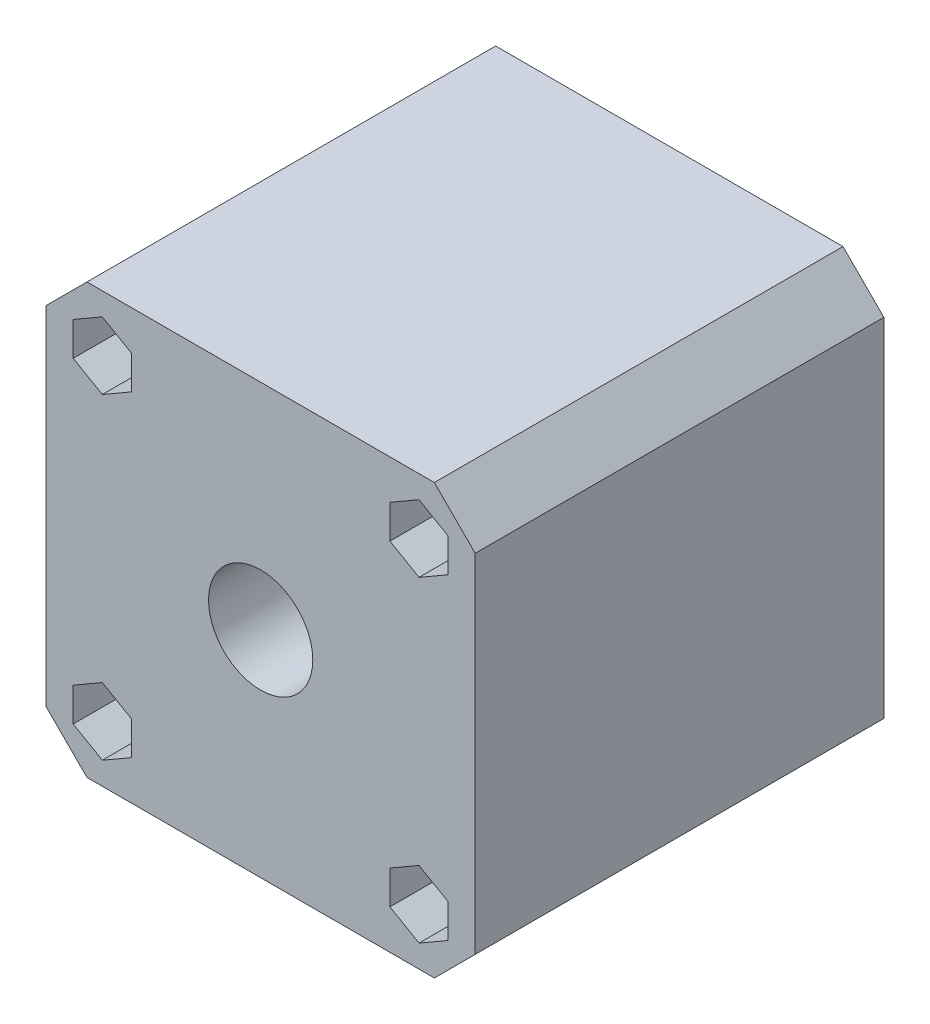
SolidWorks part; units mm, degrees
ref_plane "前基準面" through (0, 0, 0) normal (0, 0, 1) x (1, 0, 0)
ref_plane "上基準面" through (0, 0, 0) normal (0, 1, 0) x (1, 0, 0)
ref_plane "右基準面" through (0, 0, 0) normal (1, 0, 0) x (0, 0, -1)
sketch "草圖1" plane through (0, 0, 0) normal (0, 0, 1) x (1, 0, 0)
  line L0 (0, 21) -> (0, -21) construction
  line L1 (-21, 21) -> (21, 21)
  line L2 (-21, 21) -> (-21, -21)
  line L3 (-21, -21) -> (21, -21)
  line L4 (21, 21) -> (21, -21)
  line L5 (-21, 0) -> (21, 0) construction
  circle A0 centre (0, 0) radius 5.1
  circle A1 centre (-15.5, 15.5) radius 1.75
  circle A2 centre (15.5, 15.5) radius 1.75
  circle A3 centre (15.5, -15.5) radius 1.75
  circle A4 centre (-15.5, -15.5) radius 1.75
  point P7 (0, 21)
  point P8 (-21, 0)
  dimension "D1" = 10.2
  dimension "D6" = 3.5
  dimension "D2" = 42
  dimension "D3" = 42
  dimension "D4" = 5.5
  dimension "D5" = 5.5
extrude "填料-伸長1" add sketch "草圖1" along normal blind 40
chamfer "導角1" distance 4 angle 45 4 edges at (-21, -21, 20) (21, -21, 20) (21, 21, 20) (-21, 21, 20)
sketch "草圖5" plane through (0, 0, 40) normal (0, 0, -1) x (-1, 0, 0)
  line L1 (15.5, -12.2091) -> (12.65, -13.8546)
  line L2 (12.65, -13.8546) -> (12.65, -17.1454)
  line L3 (12.65, -17.1454) -> (15.5, -18.7909)
  line L4 (15.5, -18.7909) -> (18.35, -17.1454)
  line L5 (18.35, -17.1454) -> (18.35, -13.8546)
  line L6 (18.35, -13.8546) -> (15.5, -12.2091)
  line L7 (-15.5, -12.2091) -> (-18.35, -13.8546)
  line L8 (-18.35, -13.8546) -> (-18.35, -17.1454)
  line L9 (-18.35, -17.1454) -> (-15.5, -18.7909)
  line L10 (-15.5, -18.7909) -> (-12.65, -17.1454)
  line L11 (-12.65, -17.1454) -> (-12.65, -13.8546)
  line L12 (-12.65, -13.8546) -> (-15.5, -12.2091)
  line L13 (-15.5, 12.2091) -> (-12.65, 13.8546)
  line L14 (-12.65, 13.8546) -> (-12.65, 17.1454)
  line L15 (-12.65, 17.1454) -> (-15.5, 18.7909)
  line L16 (-15.5, 18.7909) -> (-18.35, 17.1454)
  line L17 (-18.35, 17.1454) -> (-18.35, 13.8546)
  line L18 (-18.35, 13.8546) -> (-15.5, 12.2091)
  line L19 (15.5, 12.2091) -> (18.35, 13.8546)
  line L20 (18.35, 13.8546) -> (18.35, 17.1454)
  line L21 (18.35, 17.1454) -> (15.5, 18.7909)
  line L22 (15.5, 18.7909) -> (12.65, 17.1454)
  line L23 (12.65, 17.1454) -> (12.65, 13.8546)
  line L24 (12.65, 13.8546) -> (15.5, 12.2091)
  circle A0 centre (15.5, -15.5) radius 2.85 construction
  circle A1 centre (-15.5, -15.5) radius 2.85 construction
  circle A2 centre (-15.5, 15.5) radius 2.85 construction
  circle A3 centre (15.5, 15.5) radius 2.85 construction
  dimension "D1" = 5.7
  dimension "D2" = 5.7
  dimension "D3" = 5.7
  dimension "D4" = 5.7
extrude "除料-伸長2" cut sketch "草圖5" along normal blind 10
sketch "草圖6" plane through (0, 0, 0) normal (0, 0, -1) x (-1, 0, 0)
  circle A0 centre (0, 0) radius 9.2
  dimension "D1" = 18.4
extrude "除料-伸長3" cut sketch "草圖6" against normal blind 1.2
sketch "草圖7" plane through (0, 0, 1.2) normal (0, 0, -1) x (-1, 0, 0)
  circle A0 centre (0, 0) radius 8.1
  dimension "D1" = 16.2
extrude "除料-伸長4" cut sketch "草圖7" against normal blind 5.2
